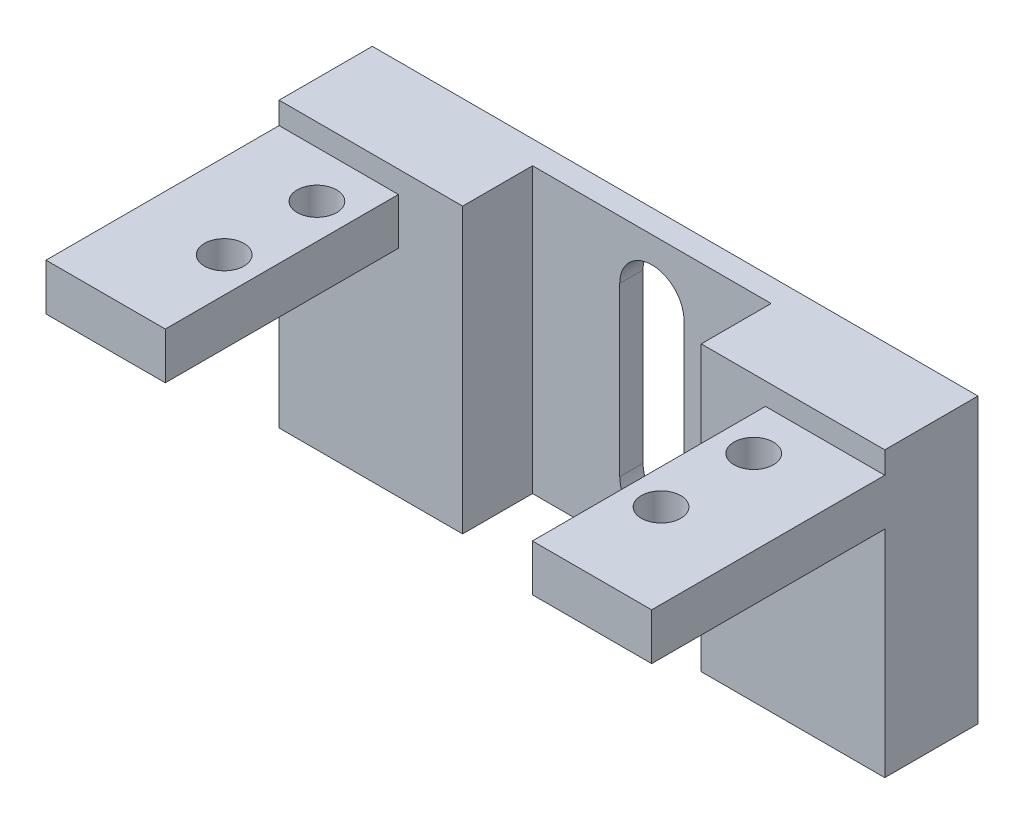
SolidWorks part; units mm, degrees
ref_plane "Front Plane" through (0, 0, 0) normal (0, 0, 1) x (1, 0, 0)
ref_plane "Top Plane" through (0, 0, 0) normal (0, 1, 0) x (1, 0, 0)
ref_plane "Right Plane" through (0, 0, 0) normal (1, 0, 0) x (0, 0, -1)
sketch "Sketch1" plane through (0, 0, 0) normal (0, 1, 0) x (1, 0, 0)
  line L1 (0, 0) -> (66, 0)
  line L2 (0, 0) -> (0, 27.62)
  line L3 (0, 27.62) -> (66, 27.62)
  line L4 (66, 0) -> (66, 27.62)
  dimension "D1" = 66
  dimension "D2" = 27.62
extrude "Boss-Extrude1" add sketch "Sketch1" along normal blind 2.54 contours L3 L4 L1 L2
sketch "Sketch2" plane through (0, 2.54, 0) normal (0, 1, 0) x (1, 0, 0)
  line L0 (0, 27.62) -> (66, 27.62)
  line L1 (66, 0) -> (66, 27.62) construction
  line L2 (0, 27.62) -> (66, 27.62) construction
  line L3 (0, 0) -> (0, 27.62) construction
  line L4 (0, 27.62) -> (0, 17.46)
  line L5 (66, 27.62) -> (66, 17.46)
  line L6 (0, 17.46) -> (20, 17.46)
  line L7 (66, 17.46) -> (46, 17.46)
  line L8 (20, 17.46) -> (20, 25.08)
  line L9 (46, 17.46) -> (46, 25.08)
  line L10 (20, 25.08) -> (46, 25.08)
  dimension "D1" = 10.16
  dimension "D2" = 20
  dimension "D3" = 2.54
extrude "Boss-Extrude2" add sketch "Sketch2" along normal blind 26 contours L6 L8 L10 L9 L7 L5 L0 L4
sketch "Sketch3" plane through (0, 0, -17.46) normal (0, 0, 1) x (1, 0, 0)
  line L0 (0, 28.54) -> (0, 23.46)
  line L1 (0, 28.54) -> (0, 2.54) construction
  line L2 (0, 28.54) -> (20, 28.54) construction
  line L3 (0, 23.46) -> (13, 23.46)
  line L4 (13, 28.54) -> (13, 23.46)
  line L5 (0, 28.54) -> (13, 28.54)
  line L7 (66, 28.54) -> (53, 28.54)
  line L8 (66, 28.54) -> (66, 23.46)
  line L9 (66, 23.46) -> (53, 23.46)
  line L10 (53, 28.54) -> (53, 23.46)
  dimension "D1" = 13
  dimension "D2" = 5.08
  dimension "D3" = 5.08
  dimension "D4" = 13
extrude "Boss-Extrude3" add sketch "Sketch3" along normal blind 25.4
sketch "Sketch4" plane through (0, 2.54, 0) normal (0, 1, 0) x (1, 0, 0)
  line L0 (46, 17.46) -> (66, 17.46)
  line L1 (0, 17.46) -> (20, 17.46)
  line L2 (0, 17.46) -> (0, 0)
  line L3 (0, 0) -> (66, 0)
  line L4 (66, 17.46) -> (66, 0)
  line L5 (20, 25.08) -> (46, 25.08)
  line L6 (20, 25.08) -> (20, 17.46)
  line L8 (46, 25.08) -> (46, 17.46)
extrude "Cut-Extrude1" cut sketch "Sketch4" against normal up to next
sketch "Sketch5" plane through (0, 28.54, 0) normal (0, 1, 0) x (1, 0, 0)
  line L0 (53, 17.46) -> (46, 17.46) construction
  line L1 (53, -7.94) -> (53, 17.46) construction
  circle A0 centre (56.8, 12.38) radius 2.15
  circle A1 centre (56.8, 2.28) radius 2.15
  dimension "D2" = 4.3
  dimension "D3" = 4.3
  dimension "D1" = 5.08
  dimension "D4" = 10.1
  dimension "D5" = 3.8
extrude "Cut-Extrude3" cut sketch "Sketch5" against normal up to next
ref_plane "Plane1" through (33, 0, 0) normal (-1, 0, 0) x (0, 0, 1)
mirror "Mirror1" about plane through (33, 0, 0) normal (-1, 0, 0) of "Cut-Extrude3"
sketch "Sketch6" plane through (0, 28.54, 0) normal (0, 1, 0) x (1, 0, 0)
  line L0 (0, 27.62) -> (66, 27.62)
  line L3 (66, 27.62) -> (66, -7.94) construction
  line L4 (0, 27.62) -> (0, -7.94) construction
  line L5 (0, 27.62) -> (0, 17.46)
  line L6 (66, 27.62) -> (66, 17.46)
  line L7 (20, 17.46) -> (0, 17.46)
  line L8 (20, 25.08) -> (20, 17.46)
  line L9 (20, 25.08) -> (46, 25.08)
  line L10 (46, 25.08) -> (46, 17.46)
  line L11 (46, 17.46) -> (66, 17.46)
extrude "Boss-Extrude4" add sketch "Sketch6" along normal blind 2.4
sketch "Sketch7" plane through (0, 0, -25.08) normal (0, 0, 1) x (1, 0, 0)
  line L0 (36.5, 24.59) -> (36.5, 6.35)
  line L1 (29.5, 24.59) -> (29.5, 6.35)
  line L2 (46, 30.94) -> (46, 0) construction
  line L3 (20, 30.94) -> (46, 30.94) construction
  line L4 (46, 0) -> (20, 0) construction
  arc A0 (36.5, 24.59) -> (29.5, 24.59) centre (33, 24.59) ccw
  arc A1 (36.5, 6.35) -> (29.5, 6.35) centre (33, 6.35) cw
  dimension "D1" = 7
  dimension "D2" = 9.5
  dimension "D3" = 6.35
  dimension "D4" = 6.35
extrude "Cut-Extrude4" cut sketch "Sketch7" against normal up to next contours A0 L1 A1 L0
